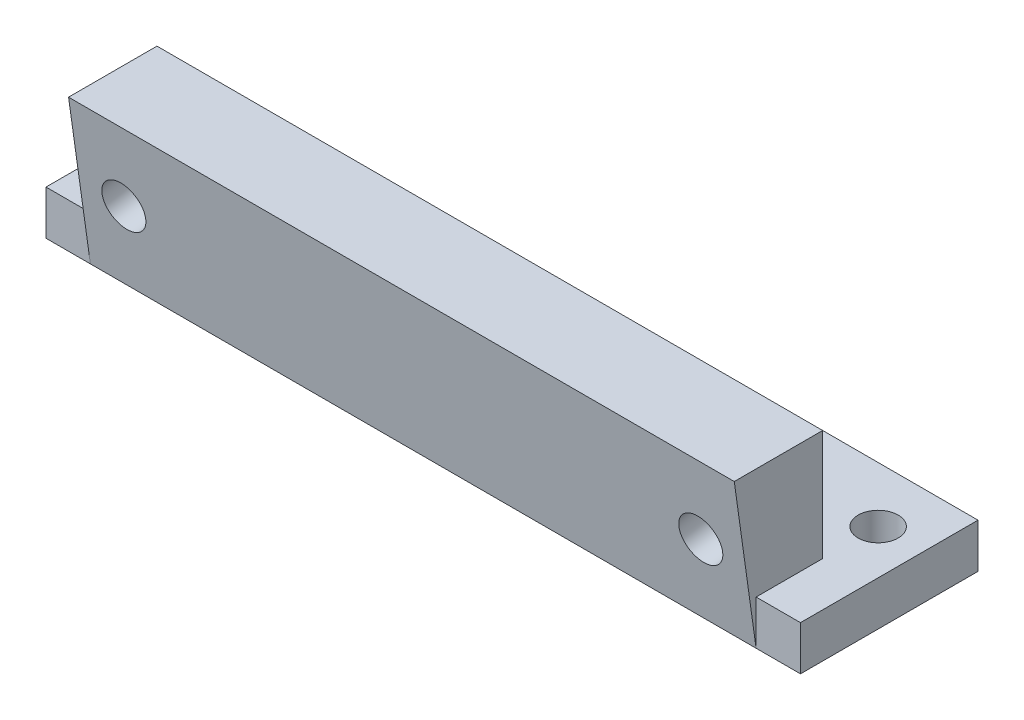
SolidWorks part; units mm, degrees
ref_plane "Front Plane" through (0, 0, 0) normal (0, 0, 1) x (1, 0, 0)
ref_plane "Top Plane" through (0, 0, 0) normal (0, 1, 0) x (1, 0, 0)
ref_plane "Right Plane" through (0, 0, 0) normal (1, 0, 0) x (0, 0, -1)
sketch "Sketch2" plane through (0, 0, 0) normal (0, 1, 0) x (1, 0, 0)
  line L1 (-21.59, -5.08) -> (21.59, -5.08)
  line L2 (-21.59, -5.08) -> (-21.59, 5.08)
  line L3 (-21.59, 5.08) -> (21.59, 5.08)
  line L4 (21.59, -5.08) -> (21.59, 5.08)
  line L5 (-21.59, -5.08) -> (21.59, 5.08) construction
  line L6 (-21.59, 5.08) -> (21.59, -5.08) construction
  point P0 (0, 0)
  dimension "D1" = 10.16
  dimension "D2" = 43.18
extrude "Boss-Extrude1" add sketch "Sketch2" along normal blind 2.54
sketch "Sketch3" plane through (0, 2.54, 0) normal (0, 1, 0) x (1, 0, 0)
  line L0 (0, -5.08) -> (0, 5.08) construction
  line L1 (-21.59, -5.08) -> (21.59, -5.08) construction
  line L2 (21.59, 5.08) -> (-21.59, 5.08) construction
  line L3 (-21.59, 5.08) -> (-21.59, -5.08) construction
  line L4 (-19.05, -5.08) -> (19.05, -5.08)
  line L5 (-19.05, -5.08) -> (-19.05, -1.27)
  line L6 (-19.05, -1.27) -> (19.05, -1.27)
  line L7 (19.05, -5.08) -> (19.05, -1.27)
  dimension "D1" = 38.1
  dimension "D2" = 2.54
  dimension "D3" = 3.81
extrude "Boss-Extrude2" add sketch "Sketch3" along normal blind 6.35
sketch "Sketch4" plane through (0, 2.54, 0) normal (0, 1, 0) x (1, 0, 0)
  line L0 (0, 5.08) -> (0, -1.27) construction
  line L1 (21.59, 5.08) -> (-21.59, 5.08) construction
  line L2 (19.05, -1.27) -> (-19.05, -1.27) construction
  line L3 (21.59, 1.905) -> (-21.59, 1.905) construction
  line L4 (-21.59, 5.08) -> (-21.59, -5.08) construction
  circle A0 centre (19.05, 1.905) radius 1.143
  circle A1 centre (-19.05, 1.905) radius 1.143
  point P11 (0, 1.905)
  dimension "D1" = 2.286
  dimension "D2" = 2.286
  dimension "D3" = 19.05
  dimension "D4" = 19.05
extrude "Cut-Extrude1" cut sketch "Sketch4" against normal through all
sketch "Sketch5" plane through (-19.05, 0, 0) normal (-1, 0, 0) x (0, 0, 1)
  line L0 (5.08, 8.89) -> (6.3294, 8.89)
  line L1 (6.3294, 8.89) -> (5.08, 0)
  line L2 (5.08, 0) -> (5.08, 8.89)
  dimension "D1" = 8
extrude "Boss-Extrude3" add sketch "Sketch5" against normal up to surface (38.1 mm away) up to face at (19.05, 6.5088, 3.6512)
sketch "Sketch6" plane through (0, -0.7001, 4.9816) normal (0, -0.1392, 0.9903) x (1, 0, 0)
  line L0 (0, 9.6844) -> (0, 0.707) construction
  line L1 (19.05, 9.6844) -> (-19.05, 9.6844) construction
  line L2 (19.05, 0.707) -> (-19.05, 0.707) construction
  line L3 (-19.05, 5.1957) -> (19.05, 5.1957) construction
  line L4 (-19.05, 0.707) -> (-19.05, 9.6844) construction
  line L5 (19.05, 9.6844) -> (19.05, 0.707) construction
  circle A0 centre (-16.51, 5.1957) radius 1.25
  circle A1 centre (16.51, 5.1957) radius 1.25
  dimension "D2" = 2.5
  dimension "D1" = 16.51
extrude "Cut-Extrude2" cut sketch "Sketch6" against normal through all
